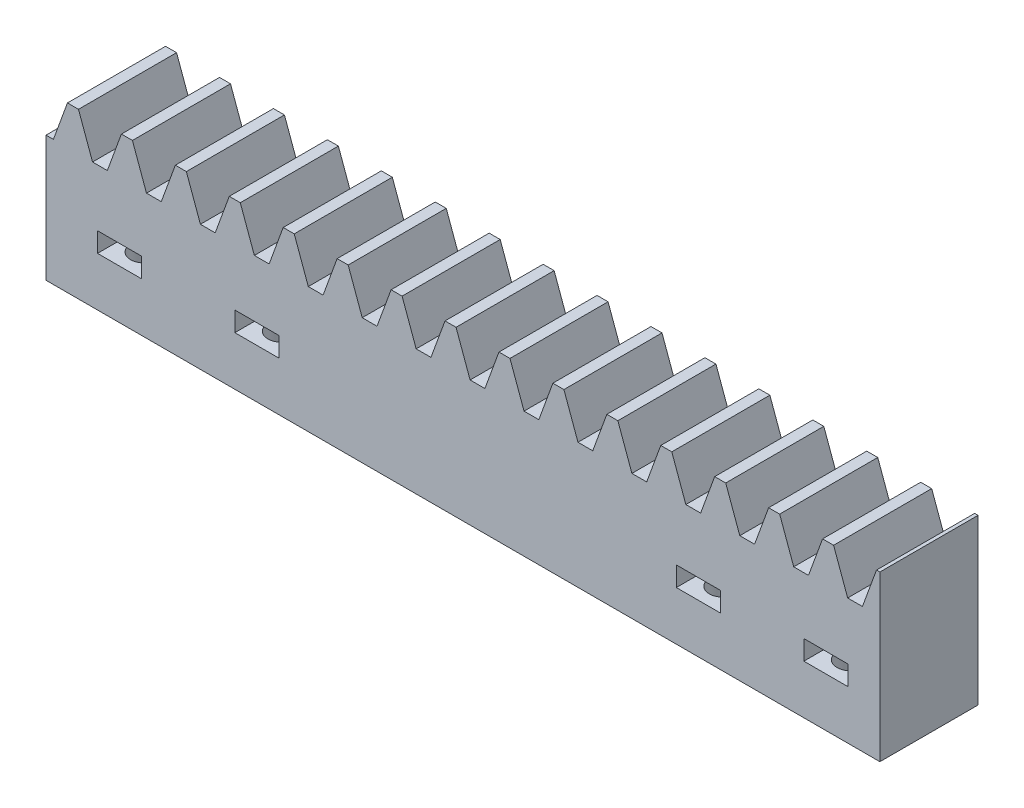
SolidWorks part; units mm, degrees
ref_plane "Plane1" through (0, 0, 0) normal (0, 0, 1) x (1, 0, 0)
ref_plane "Plane2" through (0, 0, 0) normal (0, 1, 0) x (1, 0, 0)
ref_plane "Plane3" through (0, 0, 0) normal (1, 0, 0) x (0, 0, -1)
sketch "HoldingSke" plane through (0, 0, 0) normal (0, 1, 0) x (1, 0, 0)
  line L0 (0, 0) -> (0.0398, 0.2829)
  line L1 (-15, 0) -> (100, 0) construction
  line L2 (0, 0) -> (-2.1039, 2.3779)
  line L3 (0, 0) -> (-11.863, 4.5341)
  line L4 (0, 0) -> (8.2587, 2.5249)
  line L5 (0, 0) -> (-23.7986, -8.8762)
  line L6 (0, 0) -> (-10.5278, -7.1032)
  line L9 (-71.009, 38.7566) -> (88.7388, 96.9)
  line L10 (-76.2, 5.8779) -> (-46.2, 5.8779)
  line L11 (0, 0) -> (-20, 0)
  line L12 (-76.2, 101.6) -> (-76.083, 101.6)
  line L13 (24.9733, 27.94) -> (52.9518, 28.4284)
  line L14 (24.9733, 27.94) -> (24.9743, 27.94)
  line L15 (24.9733, 27.94) -> (100.4006, 29.5858)
  circle A0 centre (0, 0) radius 19.05
  circle A1 centre (0, 0) radius 15
  circle A2 centre (0, 0) radius 12.7
  dimension "MPH" = 30
  dimension "Diameter" = 38.1
  dimension "Num_teeth" = 17
  dimension "Pitch" = 0.2857
  dimension "Width" = 20
  dimension "Show_teeth" = 998
  dimension "Thickness" = 12.7
  dimension "Ap" = 20
  dimension "Pitch_height" = 30
  dimension "Backlash" = 0.117
  dimension "Addendum_fac" = 1
  dimension "Dedendum_fac" = 1.25
  dimension "Clearance_fac" = 0.25
  dimension "Dedendum_add" = 0.001
  dimension "Length" = 170
  dimension "Module" = 3.5
sketch "BlankSke" plane through (0, 0, 0) normal (0, 0, 1) x (1, 0, 0)
  line L1 (0, 0) -> (170, 0)
  line L2 (0, 0) -> (0, 33.5)
  line L3 (0, 33.5) -> (170, 33.5)
  line L4 (170, 0) -> (170, 33.5)
  dimension "Length" = 170
  dimension "Blank_height" = 33.5
extrude "Blank" add sketch "BlankSke" against normal blind 20
sketch "TooCutSkeIll" plane through (0, 0, 0) normal (0, 0, 1) x (1, 0, 0)
  line L0 (-4.3403, 33.4079) -> (-1.7173, 26.2014)
  line L1 (-0.8941, 25.625) -> (0.8941, 25.625)
  line L2 (1.7173, 26.2014) -> (4.3403, 33.4079)
  line L3 (170, 33.5) -> (0, 33.5) construction
  line L4 (0, 0) -> (0, 64.897) construction
  line L5 (-13.208, 30) -> (12.954, 30) construction
  line L6 (0, 0) -> (170, 0) construction
  line L7 (3.0999, 30) -> (3.0999, 48.7463) construction
  line L8 (-3.0999, 30) -> (-3.0999, 48.7463) construction
  line L9 (4.4718, 33.5) -> (4.4718, 33.5254)
  line L10 (-4.4718, 33.5) -> (-4.4718, 33.5254)
  line L11 (-4.4718, 33.5254) -> (4.4718, 33.5254)
  arc A0 (0.8941, 25.625) -> (1.7173, 26.2014) centre (0.8941, 26.501) ccw
  arc A1 (-1.7173, 26.2014) -> (-0.8941, 25.625) centre (-0.8941, 26.501) ccw
  arc A2 (4.4718, 33.5) -> (4.3403, 33.4079) centre (4.4718, 33.36) ccw
  arc A3 (-4.3403, 33.4079) -> (-4.4718, 33.5) centre (-4.4718, 33.36) ccw
  dimension "Root_fillet" = 0.876
  dimension "Break_rad" = 0.14
  dimension "Pitch_height" = 30
  dimension "Gap_width" = 6.1998
  dimension "Dedendum" = 4.375
  dimension "Addendum_plus" = 3.5254
  dimension "Pressure_angle" = 20
extrude "ToothCutIll" [suppressed] cut sketch "TooCutSkeIll" against normal through all
sketch "TooCutSkeSim" plane through (0, 0, 0) normal (0, 0, 1) x (1, 0, 0)
  line L0 (1.5075, 25.625) -> (-1.5075, 25.625)
  line L1 (4.383, 33.5254) -> (1.5075, 25.625)
  line L2 (0, 17.4625) -> (0, 53.467) construction
  line L3 (4.383, 33.5254) -> (-4.383, 33.5254)
  line L6 (-4.383, 33.5254) -> (-1.5075, 25.625)
  line L9 (-3.0999, 30) -> (3.0999, 30) construction
  line L10 (0, 0) -> (170, 0) construction
  line L11 (3.0999, 30) -> (3.0999, 53.467) construction
  line L12 (-3.0999, 30) -> (-3.0999, 53.467) construction
  dimension "Pitch_height" = 30
  dimension "Pressure_angle" = 20
  dimension "Gap_width" = 6.1998
  dimension "Dedendum" = 4.375
  dimension "Addendum_plus" = 3.5254
extrude "ToothCutSim" cut sketch "TooCutSkeSim" against normal through all
pattern_linear "TeethCuts" count 16 spacing 10.9956 along (1, 0, 0) of "ToothCutIll", "ToothCutSim"
sketch "Sketch2" plane through (0, 0, 0) normal (0, 0, 1) x (1, 0, 0)
  line L0 (-8.346, 10) -> (162.7273, 10) construction
  line L1 (0, 0) -> (170, 0) construction
  line L2 (15, 21.1596) -> (15, 10) construction
  line L3 (0, 25.625) -> (0, 0) construction
  line L4 (43, 19.4948) -> (43, 10) construction
  line L5 (133, 19.4948) -> (133, 10) construction
  line L6 (159, 19.4948) -> (159, 10) construction
  line L8 (10.5, 14) -> (19.5, 14)
  line L9 (10.5, 14) -> (10.5, 10)
  line L10 (10.5, 10) -> (19.5, 10)
  line L11 (19.5, 14) -> (19.5, 10)
  line L12 (38.5, 14) -> (47.5, 14)
  line L13 (38.5, 14) -> (38.5, 10)
  line L14 (38.5, 10) -> (47.5, 10)
  line L15 (47.5, 14) -> (47.5, 10)
  line L16 (128.5, 14) -> (137.5, 14)
  line L17 (128.5, 14) -> (128.5, 10)
  line L18 (128.5, 10) -> (137.5, 10)
  line L19 (137.5, 14) -> (137.5, 10)
  line L20 (154.5, 14) -> (163.5, 14)
  line L21 (154.5, 14) -> (154.5, 10)
  line L22 (154.5, 10) -> (163.5, 10)
  line L23 (163.5, 14) -> (163.5, 10)
  dimension "D1" = 10
  dimension "D2" = 15
  dimension "D3" = 43
  dimension "D4" = 133
  dimension "D5" = 159
  dimension "D6" = 4
  dimension "D7" = 9
extrude "Cut-Extrude1" cut sketch "Sketch2" against normal blind 15
sketch "Sketch4" plane through (0, 0, 0) normal (0, -1, 0) x (1, 0, 0)
  line L0 (0, -5) -> (167.4353, -5) construction
  line L1 (0, -20) -> (0, 0) construction
  line L2 (0, 0) -> (170, 0) construction
  line L3 (15, -9.8497) -> (15, -5) construction
  circle A0 centre (15, -5) radius 2.75
  circle A1 centre (43, -5) radius 2.75
  circle A2 centre (133, -5) radius 2.75
  circle A3 centre (159, -5) radius 2.75
  dimension "D3" = 5.5
  dimension "D1" = 5
  dimension "D2" = 15
  dimension "D4" = 43
  dimension "D5" = 133
  dimension "D6" = 159
extrude "Cut-Extrude2" cut sketch "Sketch4" against normal blind 20
equation "' \"Module@HoldingSke\" = 6.35"
equation "' \"Num_teeth@HoldingSke\" = 12"
equation "' \"Ap@HoldingSke\" =  20"
equation "' \"Width@HoldingSke\" = 0.25 * 25.4"
equation "' \"Show_teeth@HoldingSke\" = 500"
equation "' \"Backlash@HoldingSke\" = 0.009 * 25.4"
equation "' \"Addendum_fac@HoldingSke\" = 1.0"
equation "' \"Dedendum_fac@HoldingSke\" = 1.25"
equation "' \"Dedendum_add@HoldingSke\" = 0.00005 * 25.4"
equation "' \"Clearance_fac@HoldingSke\" = 0.25"
equation "' \"Pitch_height@HoldingSke\" = 1 * 25.4"
equation "' \"Length@HoldingSke\" = 4.71 * 25.4"
equation "\"Pitch@HoldingSke\" = 1 / \"Module@HoldingSke\""
equation "\"MPH@HoldingSke\" = \"Dedendum_fac@HoldingSke\" / \"Pitch@HoldingSke\" + 2 * \"Dedendum_add@HoldingSke\" + 0.002 * 25.4"
equation "\"MPH@HoldingSke\" = ((sgn( \"MPH@HoldingSke\" - \"Pitch_height@HoldingSke\")+1)*( \"MPH@HoldingSke\" - \"Pitch_height@HoldingSke\"))/2 + \"Pitch_height@HoldingSke\""
equation "\"Blank_height@BlankSke\" = \"Pitch_height@HoldingSke\" + \"Addendum_fac@HoldingSke\"  / \"Pitch@HoldingSke\" "
equation "\"Length@BlankSke\" =  \"Length@HoldingSke\""
equation "\"Face_width@Blank\" = \"Width@HoldingSke\""
equation "\"Pressure_angle@TooCutSkeIll\" = \"Ap@HoldingSke\""
equation "\"Addendum_plus@TooCutSkeIll\" =  \"Addendum_fac@HoldingSke\"  / \"Pitch@HoldingSke\" + 0.001 *25.4"
equation "\"Dedendum@TooCutSkeIll\" = \"Dedendum_fac@HoldingSke\"  / \"Pitch@HoldingSke\""
equation "\"Pitch_height@TooCutSkeIll\" =  \"MPH@HoldingSke\""
equation "\"Gap_width@TooCutSkeIll\" = 3.14159265 / 2 / \"Pitch@HoldingSke\" + 6 * \"Backlash@HoldingSke\""
equation "\"Pressure_angle@TooCutSkeSim\" = \"Ap@HoldingSke\""
equation "\"Addendum_plus@TooCutSkeSim\" =  \"Addendum_fac@HoldingSke\"  / \"Pitch@HoldingSke\" + 0.001 * 25.4"
equation "\"Dedendum@TooCutSkeSim\" = \"Dedendum_fac@HoldingSke\"  / \"Pitch@HoldingSke\""
equation "\"Pitch_height@TooCutSkeSim\" =  \"MPH@HoldingSke\""
equation "\"Gap_width@TooCutSkeSim\" = 3.14159265 / 2 / \"Pitch@HoldingSke\" + 6 * \"Backlash@HoldingSke\""
equation "\"Root_fillet@TooCutSkeIll\" = \"Clearance_fac@HoldingSke\" / \"Pitch@HoldingSke\" + \"Dedendum_add@HoldingSke\""
equation "\"Break_rad@TooCutSkeIll\" = 0.02 / \"Pitch@HoldingSke\" * 2"
equation "\"Linear_pitch@TeethCuts\" = 3.14159265 / \"Pitch@HoldingSke\""
equation "\"Num_teeth@HoldingSke\" = int( ( \"Length@HoldingSke\" + 0 ) / (3.14159265 / \"Pitch@HoldingSke\")) + 0.9999  + 1"
equation " \"Num_teeth@TeethCuts\" = int( \"Show_teeth@HoldingSke\" ) + 1"
equation " \"Num_teeth@TeethCuts\" = ((sgn( \"Num_teeth@TeethCuts\" - \"Num_teeth@HoldingSke\" )-1)*( \"Num_teeth@TeethCuts\" - \"Num_teeth@HoldingSke\" ))/-2+ \"Num_teeth@HoldingSke\""
equation " \"Num_teeth@TeethCuts\" = ((sgn( \"Num_teeth@TeethCuts\" - 2.0)+1)*( \"Num_teeth@TeethCuts\" - 2.0))/2 +2.0"
